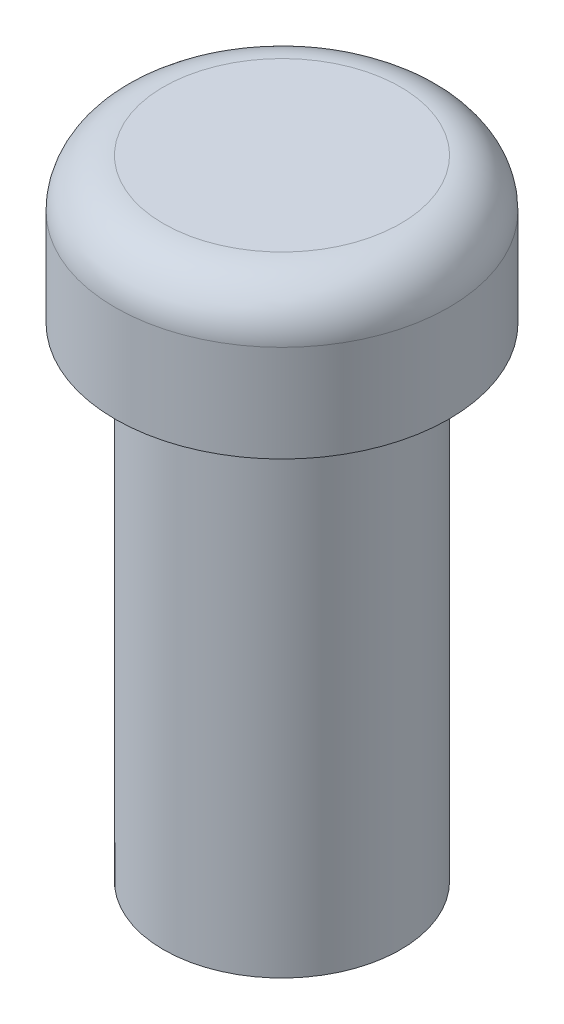
SolidWorks part; units mm, degrees
ref_plane "Front Plane" through (0, 0, 0) normal (0, 0, 1) x (1, 0, 0)
ref_plane "Top Plane" through (0, 0, 0) normal (0, 1, 0) x (1, 0, 0)
ref_plane "Right Plane" through (0, 0, 0) normal (1, 0, 0) x (0, 0, -1)
sketch "Sketch1" plane through (0, 0, 0) normal (0, 1, 0) x (1, 0, 0)
  circle A0 centre (0, 0) radius 2.45
extrude "Boss-Extrude1" add sketch "Sketch1" along normal blind 10
sketch "Sketch2" plane through (0, 10, 0) normal (0, 1, 0) x (1, 0, 0)
  circle A0 centre (0, 0) radius 3.45
extrude "Boss-Extrude2" add sketch "Sketch2" along normal blind 3
fillet "Fillet1" radius 1 1 edges at (0, 13, 3.45)
